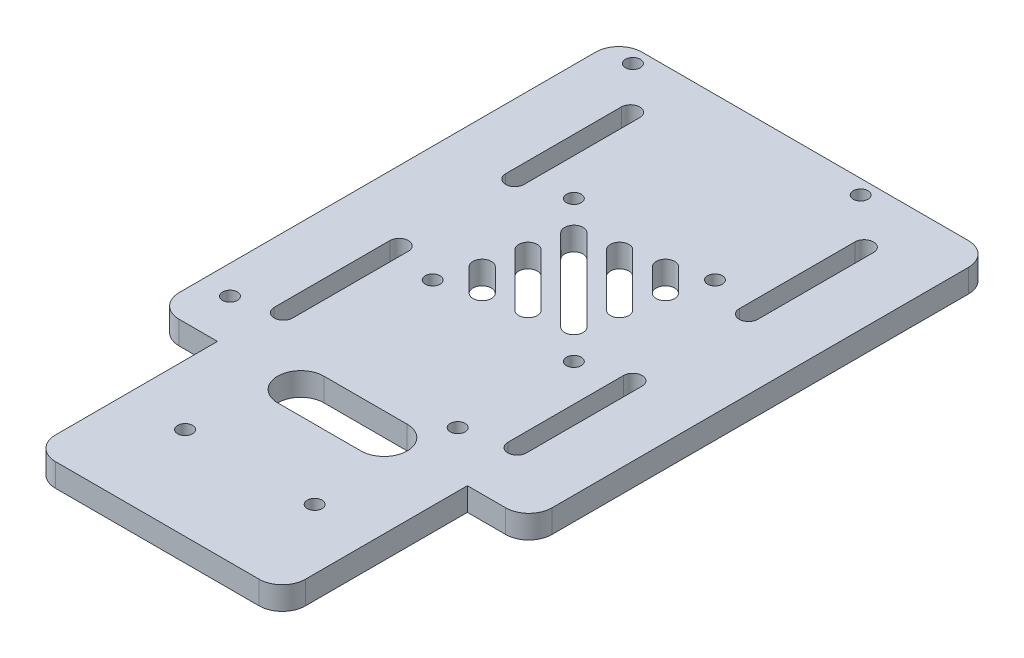
SolidWorks part; units mm, degrees
ref_plane "前视基准面" through (0, 0, 0) normal (0, 0, 1) x (1, 0, 0)
ref_plane "上视基准面" through (0, 0, 0) normal (0, 1, 0) x (1, 0, 0)
ref_plane "右视基准面" through (0, 0, 0) normal (1, 0, 0) x (0, 0, -1)
other "Configuration Table"
sketch "草图1" plane through (0, 0, 0) normal (0, 1, 0) x (1, 0, 0)
  line L0 (-40.28, 0) -> (40.28, 0) construction
  line L1 (-40.28, -50) -> (40.28, -50)
  line L2 (-40.28, -50) -> (-40.28, 50)
  line L3 (-40.28, 50) -> (40.28, 50)
  line L4 (40.28, -50) -> (40.28, 50)
  line L5 (-40.28, -50) -> (40.28, 50) construction
  line L6 (-40.28, 50) -> (40.28, -50) construction
  line L7 (0, -50) -> (0, 50) construction
  line L8 (-40.28, -50) -> (-40.28, -90) construction
  line L9 (-40.28, -90) -> (40.28, -90) construction
  line L10 (40.28, -90) -> (40.28, -50) construction
  line L11 (0, -50) -> (0, -90) construction
  line L12 (-40.28, -70) -> (40.28, -70) construction
  line L13 (-27, -90) -> (27, -90)
  line L14 (27, -90) -> (27, -50)
  line L15 (-27, -90) -> (-27, -50)
  circle A0 centre (-34.12, 46.89) radius 1.6
  circle A1 centre (15.09, 46.89) radius 1.6
  circle A2 centre (15.09, -40.19) radius 1.6
  circle A3 centre (-34.12, -40.19) radius 1.6
  circle A5 centre (-15.25, 15.25) radius 1.6
  circle A6 centre (15.25, 15.25) radius 1.6
  circle A7 centre (15.25, -15.25) radius 1.6
  circle A8 centre (-15.25, -15.25) radius 1.6
  circle A9 centre (14, -70) radius 1.6
  circle A10 centre (-14, -70) radius 1.6
  point P0 (0, 0)
  point P19 (0, 0)
  point P22 (0, 0)
  point P40 (0, -90)
  dimension "D3" = 3.2
  dimension "D10" = 3.2
  dimension "D11" = 30.5
  dimension "D12" = 30.5
  dimension "D14" = 3.2
  dimension "D1" = 80.56
  dimension "D2" = 100
  dimension "D4" = 6.16
  dimension "D5" = 3.11
  dimension "D8" = 49.21
  dimension "D9" = 87.08
  dimension "D13" = 40
  dimension "D15" = 28
  dimension "D16" = 54
  dimension "D6" = 2
  dimension "D7" = 2
extrude "凸台-拉伸1" add sketch "草图1" along normal blind 5 contours L15 L13 L14 L1 A9 A10 | L1 L4 L3 L2 A6 A5 A3 A2 A1 A0 A7 A8
sketch "草图6" plane through (0, 0, 0) normal (0, 1, 0) x (1, 0, 0)
  line L0 (0, 0) -> (50000, 0) construction
  line L1 (0, 0) -> (0, 50000) construction
  line L2 (-77.7817, 77.7817) -> (77.7817, 77.7817) construction
  line L3 (77.7817, 77.7817) -> (77.7817, -77.7817) construction
  line L4 (69.7817, 77.7817) -> (85.7817, 77.7817) construction
  line L5 (77.7817, 69.7817) -> (77.7817, 85.7817) construction
  line L6 (-77.7817, -77.7817) -> (77.7817, 77.7817) construction
  line L7 (77.7817, 91.5317) -> (64.0317, 77.7817)
  line L8 (91.5317, 77.7817) -> (77.7817, 64.0317)
  line L9 (-70.9067, 64.0317) -> (-40.28, 33.405)
  line L10 (-91.5317, -91.5317) -> (88.3498, 88.3498) construction
  line L11 (-87.5951, 87.5951) -> (77.7817, -77.7817) construction
  line L12 (40.28, -50) -> (40.28, 50)
  line L13 (40.28, 50) -> (-40.28, 50)
  line L14 (-40.28, 50) -> (-40.28, -50)
  line L15 (-40.28, -50) -> (40.28, -50)
  line L16 (-77.7817, 64.0317) -> (-70.9067, 64.0317)
  line L17 (-91.5317, 77.7817) -> (-77.7817, 64.0317)
  line L18 (-91.5317, 77.7817) -> (-91.5317, 85.1678)
  line L19 (-85.1678, 91.5317) -> (-91.5317, 85.1678)
  line L20 (-77.7817, 91.5317) -> (-85.1678, 91.5317)
  line L21 (77.7817, 91.5317) -> (85.1678, 91.5317)
  line L22 (91.5317, 77.7817) -> (91.5317, 85.1678)
  line L23 (-77.7817, 91.5317) -> (-64.0317, 77.7817)
  line L24 (-64.0317, 77.7817) -> (-64.0317, 70.9067)
  line L25 (72.1249, 83.4386) -> (83.4386, 72.1249) construction
  line L26 (77.7817, 64.0317) -> (70.9067, 64.0317)
  line L27 (64.0317, 77.7817) -> (64.0317, 70.9067)
  line L28 (77.7817, 64.0317) -> (70.9067, 64.0317)
  line L29 (64.0317, 77.7817) -> (64.0317, 70.9067)
  line L30 (64.0317, 70.9067) -> (40.28, 47.155)
  line L31 (70.9067, 64.0317) -> (40.28, 33.405)
  line L32 (85.1678, 91.5317) -> (91.5317, 85.1678)
  line L33 (-64.0317, 70.9067) -> (-40.28, 47.155)
  line L34 (-64.0317, -70.9067) -> (-40.28, -47.155)
  line L35 (-64.0317, -77.7817) -> (-64.0317, -70.9067)
  line L36 (-77.7817, -91.5317) -> (-64.0317, -77.7817)
  line L37 (-77.7817, -91.5317) -> (-85.1678, -91.5317)
  line L38 (-85.1678, -91.5317) -> (-91.5317, -85.1678)
  line L39 (-91.5317, -77.7817) -> (-91.5317, -85.1678)
  line L40 (-91.5317, -77.7817) -> (-77.7817, -64.0317)
  line L41 (-77.7817, -64.0317) -> (-70.9067, -64.0317)
  line L42 (-70.9067, -64.0317) -> (-40.28, -33.405)
  line L43 (70.9067, -64.0317) -> (40.28, -33.405)
  line L44 (77.7817, -64.0317) -> (70.9067, -64.0317)
  line L45 (91.5317, -77.7817) -> (77.7817, -64.0317)
  line L46 (91.5317, -77.7817) -> (91.5317, -85.1678)
  line L47 (85.1678, -91.5317) -> (91.5317, -85.1678)
  line L48 (77.7817, -91.5317) -> (85.1678, -91.5317)
  line L49 (77.7817, -91.5317) -> (64.0317, -77.7817)
  line L50 (64.0317, -77.7817) -> (64.0317, -70.9067)
  line L51 (64.0317, -70.9067) -> (40.28, -47.155)
  circle A0 centre (-77.7817, 77.7817) radius 65.9 construction
  circle A1 centre (77.7817, 77.7817) radius 65.9 construction
  circle A2 centre (-77.7817, -77.7817) radius 65.9 construction
  circle A3 centre (77.7817, -77.7817) radius 65.9 construction
  circle A4 centre (0, 0) radius 110 construction
  circle A5 centre (77.7817, 77.7817) radius 8 construction
  circle A6 centre (77.7817, 85.7817) radius 1.5
  circle A7 centre (85.7817, 77.7817) radius 1.5
  circle A8 centre (77.7817, 69.7817) radius 1.5
  circle A9 centre (69.7817, 77.7817) radius 1.5
  circle A10 centre (77.7817, 77.7817) radius 13.75 construction
  circle A11 centre (-77.7817, 85.7817) radius 1.5
  circle A12 centre (-85.7817, 77.7817) radius 1.5
  circle A13 centre (-69.7817, 77.7817) radius 1.5
  circle A14 centre (-77.7817, 69.7817) radius 1.5
  circle A15 centre (-77.7817, -69.7817) radius 1.5
  circle A16 centre (-69.7817, -77.7817) radius 1.5
  circle A17 centre (-85.7817, -77.7817) radius 1.5
  circle A18 centre (-77.7817, -85.7817) radius 1.5
  circle A19 centre (77.7817, -85.7817) radius 1.5
  circle A20 centre (85.7817, -77.7817) radius 1.5
  circle A21 centre (69.7817, -77.7817) radius 1.5
  circle A22 centre (77.7817, -69.7817) radius 1.5
  point P18 (77.7817, 77.7817)
  point P21 (77.7817, 77.7817)
  point P24 (0, 0)
  point P31 (77.7817, 77.7817)
  point P77 (77.7817, 77.7817)
sketch "草图7" plane through (0, 0, 0) normal (0, 1, 0) x (1, 0, 0)
  line L0 (-8.8388, 8.8388) -> (8.8388, -8.8388) construction
  line L1 (-15.25, -15.25) -> (15.25, -15.25) construction
  line L2 (-15.25, -15.25) -> (-15.25, 15.25) construction
  line L3 (-15.25, 15.25) -> (15.25, 15.25) construction
  line L4 (15.25, -15.25) -> (15.25, 15.25) construction
  line L5 (-15.25, -15.25) -> (15.25, 15.25) construction
  line L6 (-15.25, 15.25) -> (15.25, -15.25) construction
  line L7 (-7.4246, 10.253) -> (10.253, -7.4246)
  line L8 (-10.253, 7.4246) -> (7.4246, -10.253)
  line L9 (-0.7071, 10.6066) -> (10.6066, -0.7071) construction
  line L10 (0.7071, 12.0208) -> (12.0208, 0.7071)
  line L11 (-2.1213, 9.1924) -> (9.1924, -2.1213)
  line L12 (7.4246, 12.3744) -> (12.3744, 7.4246) construction
  line L13 (8.8388, 13.7886) -> (13.7886, 8.8388)
  line L14 (6.0104, 10.9602) -> (10.9602, 6.0104)
  line L15 (-12.3744, -7.4246) -> (-7.4246, -12.3744) construction
  line L16 (-13.7886, -8.8388) -> (-8.8388, -13.7886)
  line L17 (-10.9602, -6.0104) -> (-6.0104, -10.9602)
  line L18 (-10.6066, 0.7071) -> (0.7071, -10.6066) construction
  line L19 (-12.0208, -0.7071) -> (-0.7071, -12.0208)
  line L20 (-9.1924, 2.1213) -> (2.1213, -9.1924)
  line L21 (0, -50) -> (0, 50) construction
  line L22 (-40.28, 50) -> (40.28, 50) construction
  line L23 (25.25, 37.5) -> (25.25, 12.5) construction
  line L26 (-40.28, 0) -> (40.28, 0) construction
  line L27 (40.28, -50) -> (40.28, 50) construction
  line L28 (27.25, 37.5) -> (27.25, 12.5)
  line L29 (23.25, 37.5) -> (23.25, 12.5)
  line L30 (-25.25, 37.5) -> (-25.25, 12.5) construction
  line L31 (-27.25, 37.5) -> (-27.25, 12.5)
  line L32 (-23.25, 37.5) -> (-23.25, 12.5)
  line L33 (-25.25, -37.5) -> (-25.25, -12.5) construction
  line L34 (-27.25, -37.5) -> (-27.25, -12.5)
  line L35 (-23.25, -37.5) -> (-23.25, -12.5)
  line L36 (25.25, -37.5) -> (25.25, -12.5) construction
  line L37 (27.25, -37.5) -> (27.25, -12.5)
  line L38 (23.25, -37.5) -> (23.25, -12.5)
  line L39 (-27, -50) -> (27, -50) construction
  line L40 (-9, -50) -> (9, -50) construction
  line L41 (-9, -45) -> (9, -45)
  line L42 (-9, -55) -> (9, -55)
  arc A0 (-7.4246, 10.253) -> (-10.253, 7.4246) centre (-8.8388, 8.8388) ccw
  arc A1 (7.4246, -10.253) -> (10.253, -7.4246) centre (8.8388, -8.8388) ccw
  arc A2 (0.7071, 12.0208) -> (-2.1213, 9.1924) centre (-0.7071, 10.6066) ccw
  arc A3 (9.1924, -2.1213) -> (12.0208, 0.7071) centre (10.6066, -0.7071) ccw
  arc A4 (8.8388, 13.7886) -> (6.0104, 10.9602) centre (7.4246, 12.3744) ccw
  arc A5 (10.9602, 6.0104) -> (13.7886, 8.8388) centre (12.3744, 7.4246) ccw
  arc A6 (-13.7886, -8.8388) -> (-10.9602, -6.0104) centre (-12.3744, -7.4246) cw
  arc A7 (-6.0104, -10.9602) -> (-8.8388, -13.7886) centre (-7.4246, -12.3744) cw
  arc A8 (-12.0208, -0.7071) -> (-9.1924, 2.1213) centre (-10.6066, 0.7071) cw
  arc A9 (2.1213, -9.1924) -> (-0.7071, -12.0208) centre (0.7071, -10.6066) cw
  arc A12 (27.25, 37.5) -> (23.25, 37.5) centre (25.25, 37.5) ccw
  arc A13 (23.25, 12.5) -> (27.25, 12.5) centre (25.25, 12.5) ccw
  arc A14 (-27.25, 37.5) -> (-23.25, 37.5) centre (-25.25, 37.5) cw
  arc A15 (-23.25, 12.5) -> (-27.25, 12.5) centre (-25.25, 12.5) cw
  arc A16 (-27.25, -37.5) -> (-23.25, -37.5) centre (-25.25, -37.5) ccw
  arc A17 (-23.25, -12.5) -> (-27.25, -12.5) centre (-25.25, -12.5) ccw
  arc A18 (27.25, -37.5) -> (23.25, -37.5) centre (25.25, -37.5) cw
  arc A19 (23.25, -12.5) -> (27.25, -12.5) centre (25.25, -12.5) cw
  arc A20 (-9, -45) -> (-9, -55) centre (-9, -50) ccw
  arc A21 (9, -55) -> (9, -45) centre (9, -50) ccw
  point P0 (0, 0)
  point P9 (0, 0)
  point P16 (4.9497, 4.9497)
  point P21 (9.8995, 9.8995)
  point P31 (-9.8995, -9.8995)
  point P38 (-4.9497, -4.9497)
  point P47 (0, 0)
  point P49 (25.25, 25)
  point P59 (0, 0)
  point P62 (-25.25, 25)
  point P64 (25.25, 25)
  point P70 (-25.25, -25)
  point P77 (25.25, -25)
  point P87 (0, -50)
  dimension "D3" = 4
  dimension "D7" = 2
  dimension "D9" = 25
  dimension "D10" = 2
  dimension "D13" = 10
  dimension "D1" = 4
  dimension "D2" = 25
  dimension "D4" = 3
  dimension "D5" = 16
  dimension "D6" = 7
  dimension "D8" = 3
  dimension "D11" = 25
  dimension "D12" = 10
  dimension "D15" = 18
extrude "切除-拉伸5" cut sketch "草图7" along normal through all contours A7 L17 A6 L16 | A9 L20 A8 L19 | L8 A1 L7 A0 | L11 A3 L10 A2 | L14 A5 L13 A4 | A15 L32 A14 L31 | L29 A13 L28 A12 | L35 A17 L34 A16 | A19 L38 A18 L37 | L42 A21 L41 A20
sketch "草图8" plane through (0, 0, 0) normal (0, 1, 0) x (1, 0, 0)
  line L0 (0, 0) -> (0, 82.5) construction
  line L1 (-40.28, 50) -> (40.28, 50) construction
  line L2 (-22, 115) -> (22, 115)
  line L3 (-22, 115) -> (-22, 50)
  line L4 (-22, 50) -> (22, 50)
  line L5 (22, 115) -> (22, 50)
  line L6 (-22, 115) -> (22, 50) construction
  line L7 (-22, 50) -> (22, 115) construction
  line L8 (11, 50) -> (11, 115) construction
  line L9 (-7.5, 57.5) -> (7.5, 57.5) construction
  line L10 (-7.5, 60) -> (7.5, 60)
  line L11 (-7.5, 55) -> (7.5, 55)
  circle A0 centre (11, 105) radius 1.6
  circle A1 centre (-11, 105) radius 1.6
  circle A2 centre (11, 82.63) radius 1.6
  circle A3 centre (-11, 82.63) radius 1.6
  arc A4 (-7.5, 60) -> (-7.5, 55) centre (-7.5, 57.5) ccw
  arc A5 (7.5, 55) -> (7.5, 60) centre (7.5, 57.5) ccw
  point P21 (0, 57.5)
  dimension "D4" = 3.2
  dimension "D6" = 3.2
  dimension "D9" = 2.5
  dimension "D1" = 65
  dimension "D2" = 44
  dimension "D3" = 11
  dimension "D5" = 10
  dimension "D7" = 22.37
  dimension "D8" = 15
  dimension "D10" = 5
fillet "圆角1" radius 5 6 edges at (27, 2.5, 90) (40.28, 2.5, 50) (40.28, 2.5, -50) (-40.28, 2.5, -50) (-40.28, 2.5, 50) (-27, 2.5, 90)
